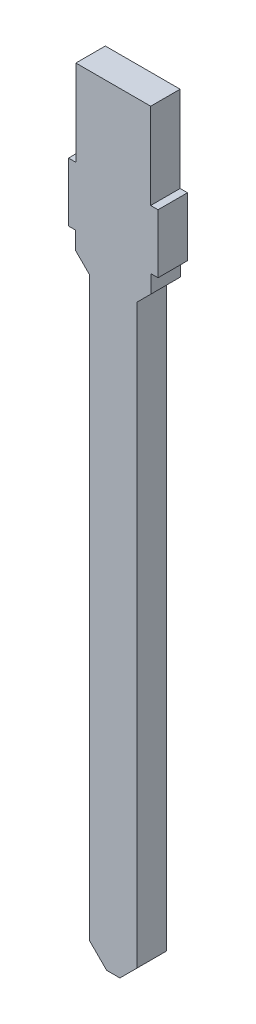
SolidWorks part; units mm, degrees
ref_plane "Front Plane" through (0, 0, 0) normal (0, 0, 1) x (1, 0, 0)
ref_plane "Top Plane" through (0, 0, 0) normal (0, 1, 0) x (1, 0, 0)
ref_plane "Right Plane" through (0, 0, 0) normal (1, 0, 0) x (0, 0, -1)
sketch "Sketch1" plane through (0, 0, 0) normal (0, 0, 1) x (1, 0, 0)
  line L0 (0, 0) -> (0, 53.4998) construction
  line L1 (-0.635, 13.08) -> (0.635, 13.08)
  line L2 (0.635, 13.08) -> (0.635, 11.62)
  line L3 (0.635, 11.62) -> (0.76, 11.62)
  line L4 (0.76, 11.62) -> (0.76, 10.62)
  line L5 (0.76, 10.62) -> (0.643, 10.62)
  line L6 (0.643, 10.62) -> (0.643, 10.323)
  line L7 (0.643, 10.323) -> (0.4, 10.08)
  line L8 (0.4, 10.08) -> (0.4, 0.2878)
  line L9 (0.1122, 0) -> (-0.1122, 0)
  line L10 (0.4, 0.2878) -> (0.1122, 0)
  line L11 (-0.4, 0.2878) -> (-0.1122, 0)
  line L12 (-0.4, 10.08) -> (-0.4, 0.2878)
  line L13 (-0.643, 10.323) -> (-0.4, 10.08)
  line L14 (-0.643, 10.62) -> (-0.643, 10.323)
  line L15 (-0.76, 10.62) -> (-0.643, 10.62)
  line L16 (-0.76, 11.62) -> (-0.76, 10.62)
  line L17 (-0.635, 11.62) -> (-0.76, 11.62)
  line L18 (-0.635, 13.08) -> (-0.635, 11.62)
  point P22 (0, 13.08)
  dimension "D1" = 0.635
  dimension "D2" = 1.46
  dimension "D3" = 1
  dimension "D4" = 0.76
  dimension "D5" = 0.4
  dimension "D7" = 13.08
  dimension "D8" = 0.643
extrude "Boss-Extrude1" add sketch "Sketch1" along normal blind 0.5
